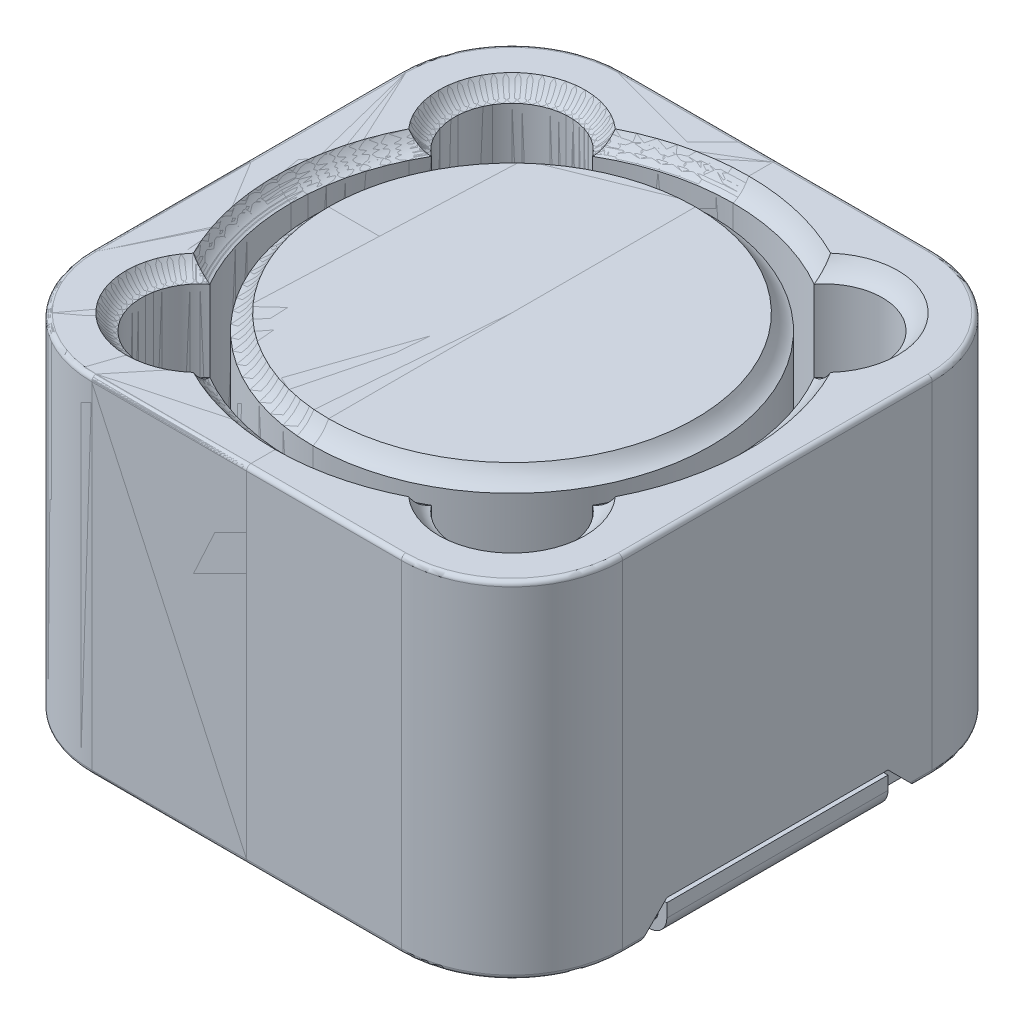
SolidWorks part; units mm, degrees
ref_plane "Спереди" through (0, 0, 0) normal (0, 0, 1) x (1, 0, 0)
ref_plane "Сверху" through (0, 0, 0) normal (0, 1, 0) x (1, 0, 0)
ref_plane "Справа" through (0, 0, 0) normal (1, 0, 0) x (0, 0, -1)
sketch "Эскиз1" plane through (0, 0, 0) normal (0, 1, 0) x (1, 0, 0)
  line L0 (0, 102.542) -> (0, 0) construction
  line L1 (-99.9825, 0) -> (0, 0) construction
  line L2 (-3.5, 9.4779) -> (-3.5, 0) construction
  line L3 (-3.5, 6) -> (0, 6)
  line L4 (-6, 3.5) -> (-6, 0)
  line L8 (-13.5627, 3.5) -> (0, 3.5) construction
  line L10 (-6, 0) -> (0, 0)
  line L11 (0, 0) -> (0, 6)
  arc A0 (-6, 3.5) -> (-3.5, 6) centre (-3.5, 3.5) cw
extrude "Вытянуть1" add sketch "Эскиз1" along normal blind 7.8
sketch "Эскиз2" plane through (0, 7.8, 0) normal (0, 1, 0) x (1, 0, 0)
  line L1 (713.4707, 713.4707) -> (4.4548, 4.4548) construction
  line L2 (0, 0) -> (0, 6) construction
  line L3 (-6, 0) -> (0, 0) construction
  line L4 (0, 4.5) -> (0, 5)
  line L5 (-5, 0) -> (-4.5, 0)
  line L7 (-3.182, 3.182) -> (-10.56, 10.56) construction
  arc A0 (-4.3275, 2.5046) -> (-5, 0) centre (0, 0) ccw
  arc A1 (0, 4.5) -> (-4.5, 0) centre (0, 0) ccw
  arc A2 (-2.5046, 4.3275) -> (-4.3275, 2.5046) centre (-3.5355, 3.5355) ccw
  arc A6 (0, 5) -> (-2.5046, 4.3275) centre (0, 0) ccw
  dimension "D1" = 10
  dimension "D2" = 9
extrude "Вытянуть2" cut sketch "Эскиз2" against normal blind 5
sketch "Эскиз3" plane through (0, 0, 0) normal (0, 0, 1) x (1, 0, 0)
  line L1 (-4.5, 2.8) -> (-4.5, 7.8) construction
  line L2 (-4.5, 7.8) -> (0, 7.8) construction
  line L4 (-6, 7.8) -> (-5, 7.8) construction
  line L5 (-5, 2.8) -> (-5, 7.8) construction
  line L6 (-5, 7.4464) -> (-5, 7.8)
  line L7 (-5, 7.8) -> (-5.3536, 7.8)
  line L8 (-4.5, 7.4464) -> (-4.5, 7.8)
  line L9 (-4.5, 7.8) -> (-4.1464, 7.8)
  spline S1 degree 2 poles (-5.3536, 7.8) (-5.2134, 7.5348) (-5, 7.4464) knots 0 0 0 0.5 0.5 0.5
  spline S2 degree 2 poles (-4.1464, 7.8) (-4.2866, 7.5348) (-4.5, 7.4464) knots 0 0 0 0.5 0.5 0.5
  dimension "D3" = 0.5
revolve "Вырез-Повернуть1" cut sketch "Эскиз3" angle 360 about axis through (0, 7.8, 0) along (0, -1, 0)
ref_point "Точка1"
ref_plane "Плоскость2" through (-3.5355, 0, 0) normal (1, 0, 0) x (0, 0, -1)
sketch "Эскиз5" plane through (-3.5355, 0, 0) normal (1, 0, 0) x (0, 0, -1)
  line L0 (3.5355, 8.907) -> (3.5355, -1.4651) construction
  line L5 (4.8355, 8.2925) -> (4.8355, 7.0284) construction
  line L6 (4.8355, 7.8) -> (4.8355, 7.4464)
  line L7 (4.8355, 7.8) -> (5.1891, 7.8)
  line L8 (5.3536, 7.8) -> (4.5835, 7.8) construction
  spline S1 degree 3 poles (4.8355, 7.4464) (4.9139, 7.4724) (4.9822, 7.5212) (5.0978, 7.6445) (5.1466, 7.7194) (5.1891, 7.8) knots 0 0 0 0 0.5 0.5 1 1 1 1
revolve "Вырез-Повернуть2" cut sketch "Эскиз5" angle 61 about L0 other way angle 154
fillet "Скругление1" radius 0.1 6 edges at (-1.75, 0, -6) (-6, 0, -1.75) (-6, 7.8, -1.75) (-5.2678, 7.8, -5.2678) (-5.2678, 0, -5.2678) (-1.75, 7.8, -6)
pattern_circular "Круговой массив1" count 4 over 360 about axis through (0, 7.8, 0) along (0, -1, 0) of bodies 105
sketch "Эскиз7" plane through (6, 0, 0) normal (1, 0, 0) x (0, 0, -1)
  line L1 (-3.1, 0) -> (3.1, 0)
  line L3 (-2.5, 0.6) -> (2.5, 0.6)
  line L5 (0, -1.5137) -> (0, 8.5305) construction
  line L6 (-3.1, 0) -> (-2.5, 0.6)
  line L8 (0, 0) -> (-3.5, 0) construction
  line L9 (3.1, 0) -> (2.5, 0.6)
extrude "Вытянуть3" cut sketch "Эскиз7" against normal blind 0.3
mirror "Зеркальное отражение1" about plane through (0, 0, 0) normal (1, 0, 0) of "Вытянуть3"
sketch "Эскиз8" plane through (0, 0, 0) normal (0, 0, 1) x (1, 0, 0)
  line L0 (0, -1.3448) -> (0, 8.4383) construction
  line L1 (6, 7.7) -> (6, 0.1) construction
  line L2 (6, 0.5) -> (5.8, 0.5)
  line L5 (5.8, 0.5) -> (5.8, 0.2)
  line L7 (5.6, -0.2) -> (3.8, -0.2)
  line L8 (6, 0.2) -> (6, 0.5)
  line L9 (5.6, 0) -> (3.8, 0)
  line L10 (3.8, -0.2) -> (3.8, 0)
  arc A0 (5.8, 0.2) -> (5.6, 0) centre (5.6, 0.2) cw
  arc A1 (6, 0.2) -> (5.6, -0.2) centre (5.6, 0.2) cw
  dimension "D3" = 0.2
  dimension "D4" = 0.4
  dimension "D1" = 0.2
  dimension "D2" = 0.2
  dimension "D5" = 0.5
  dimension "D6" = 2.2
extrude "Вытянуть4" add sketch "Эскиз8" along normal blind 2.5 and the other way blind 2.5
mirror "Зеркальное отражение5" about plane through (0, 0, 0) normal (1, 0, 0) of bodies 115
